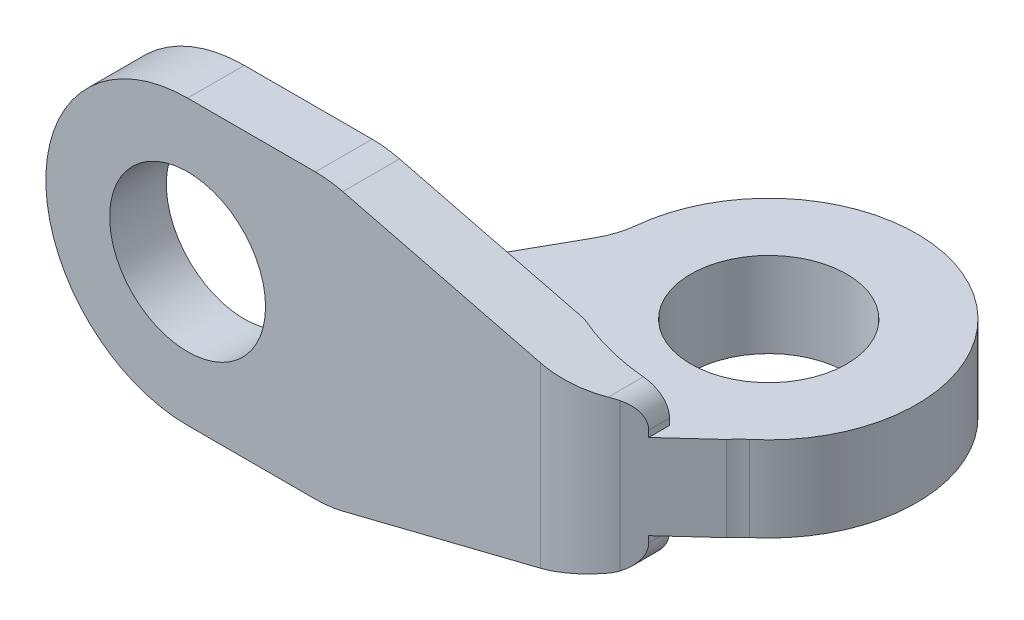
SolidWorks part; units mm, degrees
ref_plane "前视基准面" through (0, 0, 0) normal (0, 0, 1) x (1, 0, 0)
ref_plane "上视基准面" through (0, 0, 0) normal (0, 1, 0) x (1, 0, 0)
ref_plane "右视基准面" through (0, 0, 0) normal (1, 0, 0) x (0, 0, -1)
other "Configuration Table"
sketch "Sketch1" plane through (0, 0, 0) normal (0, 0, 1) x (1, 0, 0)
  line L0 (0, -5) -> (5, -5) construction
  line L1 (0, 0) -> (9.5088, 0)
  line L2 (0, 0) -> (0, -10)
  line L3 (0, -10) -> (9.5088, -10)
  line L4 (20, -2.5) -> (20, -6.7192)
  line L5 (20, -4.6096) -> (20, -3.2808)
  line L6 (19.2425, -2.3106) -> (10.4765, -0.1191)
  line L7 (20, -4.6096) -> (20, -7.5)
  line L8 (19.2425, -7.6894) -> (10.4765, -9.8809)
  arc A1 (5, 0) -> (5, -10) centre (5, -5) ccw
  arc A2 (10.4765, -9.8809) -> (9.5088, -10) centre (9.5088, -6.01) cw
  arc A3 (10.4765, -0.1191) -> (9.5088, 0) centre (9.5088, -3.99) ccw
  arc A4 (19.2425, -7.6894) -> (20, -6.7192) centre (19, -6.7192) ccw
  arc A5 (19.2425, -2.3106) -> (20, -3.2808) centre (19, -3.2808) cw
  circle A6 centre (5, -5) radius 2.75
  dimension "D5" = 3.99
  dimension "D6" = 1
  dimension "D7" = 5.5
  dimension "D1" = 5
  dimension "D2" = 10
  dimension "D3" = 5
  dimension "D4" = 2.5
extrude "Boss-Extrude1" add sketch "Sketch1" along normal blind 2
ref_plane "Plane1" through (0, -4, 0) normal (0, -1, 0) x (-1, 0, 0)
sketch "Sketch3" plane through (0, -4, 0) normal (0, -1, 0) x (-1, 0, 0)
  line L0 (-20, 0) -> (-20, 5)
  line L1 (-20, 5) -> (-18.5, 5)
  line L2 (-18.5, 5) -> (-10.4765, 0)
  line L3 (-13.2798, 5) -> (-10.4765, 0)
  line L4 (-23.7202, 5) -> (-20, -2)
  line L5 (-20, -2) -> (-10.4765, 0)
  circle A0 centre (-18.5, 5) radius 2.75
  circle A1 centre (-18.5, 5) radius 5.2202
  dimension "D3" = 5.5
  dimension "D1" = 1.5
  dimension "D2" = 5
extrude "Boss-Extrude2" add sketch "Sketch3" along normal blind 2.5 and the other way blind 0.5 contours L4 A1 | L4 A1 L0 A0 L2 | L0 A1 L2 A0 | A1 L2 L3 | A1 L4 L5 L2
fillet "Fillet1" radius 3 3 edges at (21.4208, -5, -0.6735) (10.4765, -5, 0) (13.2798, -5, -5)
sketch "Sketch4" plane through (0, -4, 0) normal (0, -1, 0) x (-1, 0, 0)
  line L0 (-21.4325, 0.5757) -> (-18.6132, -2)
  line L1 (-19.2425, -2) -> (-10.4765, -2) construction
  line L2 (-21.4325, 0.5757) -> (-20, -2)
  line L3 (-20, -2) -> (-18.6132, -2)
  arc A0 (-21.1115, 0.0915) -> (-21.8408, 0.9888) centre (-23.7607, -1.3163) ccw construction
extrude "Cut-Extrude1" cut sketch "Sketch4" against normal blind 3.5 and the other way blind 4.9
fillet "Fillet2" radius 3 1 edges at (18.6132, -5, 2)
sketch "Sketch5" plane through (0, -6.5, 0) normal (0, -1, 0) x (1, 0, 0)
  circle A1 centre (18.5, -5) radius 5.2202
extrude "Cut-Extrude2" cut sketch "Sketch5" along normal blind 3.5
sketch "Sketch6" plane through (0, -3.5, 0) normal (0, 1, 0) x (1, 0, 0)
  circle A1 centre (18.5, 5) radius 5.2211
extrude "Cut-Extrude3" cut sketch "Sketch6" along normal blind 3.5
